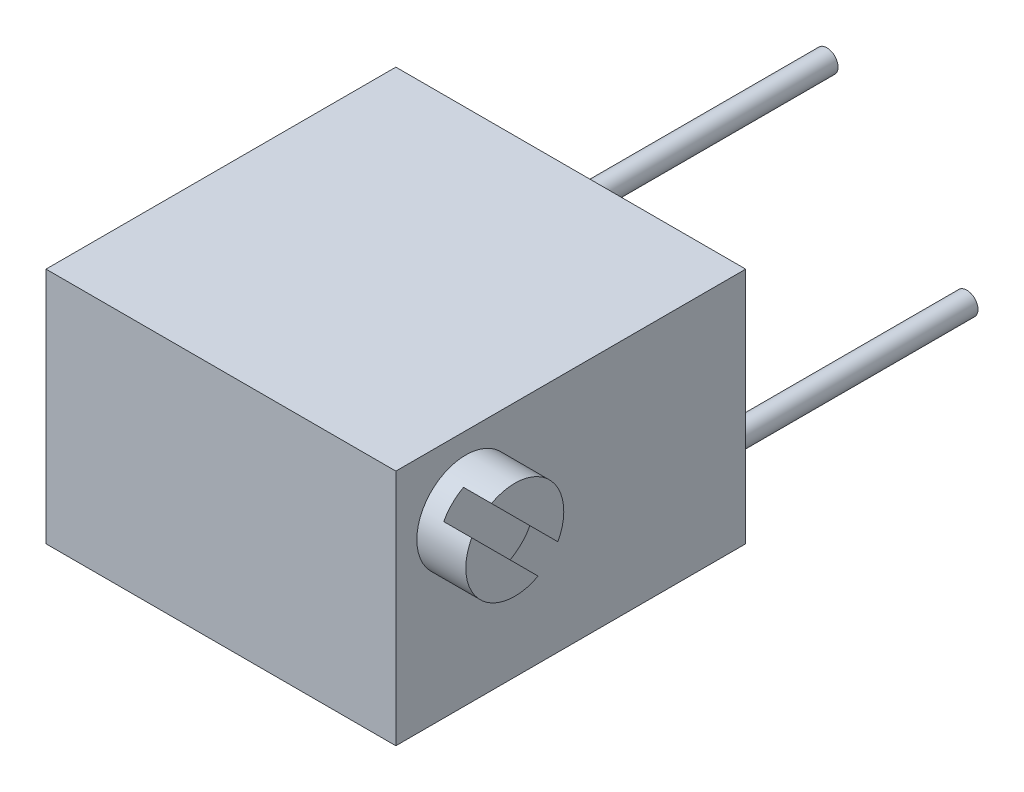
SolidWorks part; units mm, degrees
ref_plane "Front Plane" through (0, 0, 0) normal (0, 0, 1) x (1, 0, 0)
ref_plane "Top Plane" through (0, 0, 0) normal (0, 1, 0) x (1, 0, 0)
ref_plane "Right Plane" through (0, 0, 0) normal (1, 0, 0) x (0, 0, -1)
sketch "Sketch2" plane through (0, 0, 0) normal (0, 0, 1) x (1, 0, 0)
  line L0 (-0.508, -3.302) -> (5.842, -3.302)
  line L1 (5.842, -3.302) -> (5.842, 1.016)
  line L2 (5.842, 1.016) -> (-0.508, 1.016)
  line L3 (-0.508, 1.016) -> (-0.508, -3.302)
  dimension "D1" = 6.35
  dimension "D2" = 4.318
  dimension "D3" = 1.016
  dimension "D4" = 0.508
extrude "Boss-Extrude1" add sketch "Sketch2" along normal blind 6.35
sketch "Sketch3" plane through (5.842, 0, 0) normal (1, 0, 0) x (0, 0, -1)
  line L0 (-6.35, 1.016) -> (0, 1.016) construction
  line L1 (-6.35, -3.302) -> (-6.35, 1.016) construction
  circle A0 centre (-5.08, -0.254) radius 0.889
  dimension "D1" = 1.778
  dimension "D2" = 1.27
  dimension "D3" = 1.27
extrude "Boss-Extrude2" add sketch "Sketch3" along normal blind 0.889
sketch "Sketch4" plane through (6.731, 0, 0) normal (1, 0, 0) x (0, 0, -1)
  line L1 (-4.298, -0.6768) -> (-5.5028, 0.528)
  line L2 (-4.6572, -1.036) -> (-5.862, 0.1688)
  arc A0 (-4.6572, -1.036) -> (-4.298, -0.6768) centre (-5.08, -0.254) ccw
  arc A1 (-5.5028, 0.528) -> (-5.862, 0.1688) centre (-5.08, -0.254) ccw
extrude "Cut-Extrude1" cut sketch "Sketch4" against normal blind 0.508
sketch "Sketch8" plane through (0, 0, 0) normal (0, 0, -1) x (-1, 0, 0)
  line L0 (0.508, 1.016) -> (0.508, -3.302) construction
  line L1 (0.508, -3.302) -> (-5.842, -3.302) construction
  circle A0 centre (0, -2.286) radius 0.2032
  circle A1 centre (-5.08, -2.286) radius 0.2032
  circle A2 centre (-2.54, 0.254) radius 0.2032
  dimension "D2" = 0.4064
  dimension "D4" = 0.4064
  dimension "D5" = 0.4064
  dimension "D1" = 0.508
  dimension "D3" = 5.08
  dimension "D6" = 2.54
  dimension "D7" = 2.54
  dimension "D8" = 1.016
extrude "Boss-Extrude3" add sketch "Sketch8" along normal blind 4.7752
